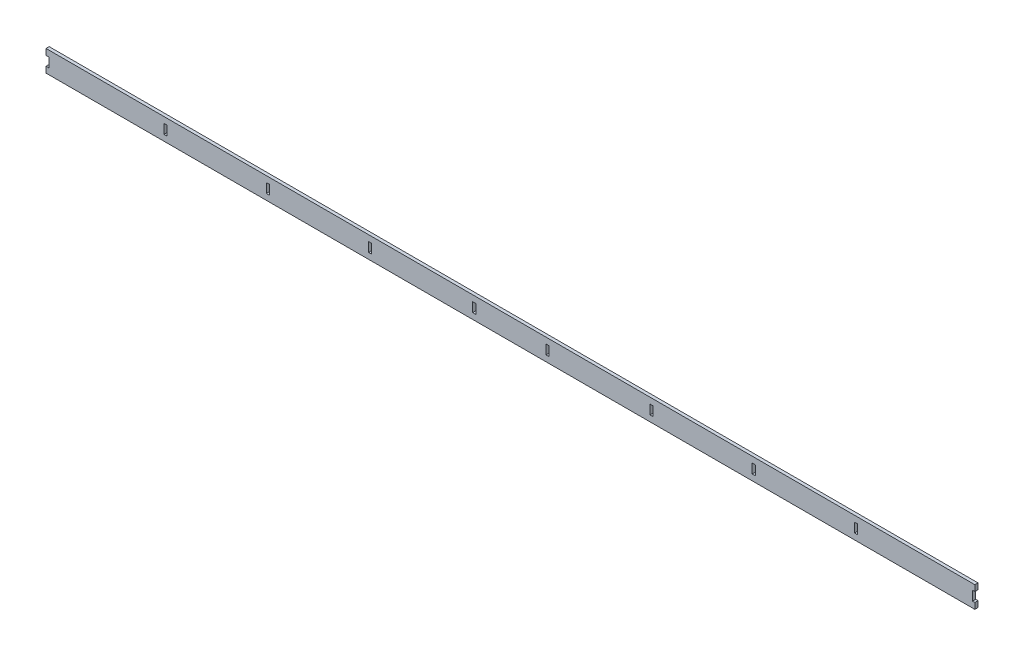
SolidWorks part; units mm, degrees
ref_plane "前视基准面" through (0, 0, 0) normal (0, 0, 1) x (1, 0, 0)
ref_plane "上视基准面" through (0, 0, 0) normal (0, 1, 0) x (1, 0, 0)
ref_plane "右视基准面" through (0, 0, 0) normal (1, 0, 0) x (0, 0, -1)
sketch "Model" plane through (0, 0, 0) normal (0, 0, 1) x (1, 0, 0)
  line L0 (587.3644, 20.9364) -> (-2.9318, 20.9364)
  line L1 (-2.9318, 20.9364) -> (-2.9318, 17.1364)
  line L2 (-2.9318, 11.1364) -> (-2.9318, 7.3364)
  line L3 (-2.9318, 7.3364) -> (587.3644, 7.3364)
  line L4 (587.3644, 20.9364) -> (587.3644, 17.1364)
  line L5 (587.3644, 11.1364) -> (587.3644, 7.3364)
  line L6 (587.3644, 17.1364) -> (585.8644, 17.1364)
  line L7 (585.8644, 17.1364) -> (585.8644, 11.1364)
  line L8 (585.8644, 11.1364) -> (587.3644, 11.1364)
  line L9 (-2.9318, 17.1364) -> (-0.9318, 17.1364)
  line L10 (-0.9318, 17.1364) -> (-0.9318, 11.1364)
  line L11 (-0.9318, 11.1364) -> (-2.9318, 11.1364)
  line L12 (72.0681, 14.1364) -> (72.0681, 17.1364)
  line L13 (72.0681, 11.1364) -> (72.0681, 14.1364)
  line L14 (137.0681, 14.1364) -> (137.0681, 17.1364)
  line L15 (137.0681, 11.1364) -> (137.0681, 14.1364)
  line L16 (202.0681, 14.1364) -> (202.0681, 17.1364)
  line L17 (202.0681, 11.1364) -> (202.0681, 14.1364)
  line L18 (268.2681, 14.1364) -> (268.2681, 17.1364)
  line L19 (268.2681, 11.1364) -> (268.2681, 14.1364)
  line L20 (314.7681, 14.1364) -> (314.7681, 17.1364)
  line L21 (314.7681, 11.1364) -> (314.7681, 14.1364)
  line L22 (380.8645, 14.1364) -> (380.8645, 17.1364)
  line L23 (380.8645, 11.1364) -> (380.8645, 14.1364)
  line L24 (445.8645, 14.1364) -> (445.8645, 17.1364)
  line L25 (445.8645, 11.1364) -> (445.8645, 14.1364)
  line L26 (510.8644, 14.1364) -> (510.8644, 17.1364)
  line L27 (510.8644, 11.1364) -> (510.8644, 14.1364)
  line L28 (72.0681, 17.1364) -> (74.0681, 17.1364)
  line L29 (74.0681, 17.1364) -> (74.0681, 11.1364)
  line L30 (74.0681, 11.1364) -> (72.0681, 11.1364)
  line L31 (137.0681, 17.1364) -> (139.0681, 17.1364)
  line L32 (139.0681, 17.1364) -> (139.0681, 11.1364)
  line L33 (139.0681, 11.1364) -> (137.0681, 11.1364)
  line L34 (202.0681, 17.1364) -> (204.0681, 17.1364)
  line L35 (204.0681, 17.1364) -> (204.0681, 11.1364)
  line L36 (204.0681, 11.1364) -> (202.0681, 11.1364)
  line L37 (268.2681, 17.1364) -> (270.2681, 17.1364)
  line L38 (270.2681, 17.1364) -> (270.2681, 11.1364)
  line L39 (270.2681, 11.1364) -> (268.2681, 11.1364)
  line L40 (314.7681, 17.1364) -> (316.7681, 17.1364)
  line L41 (316.7681, 17.1364) -> (316.7681, 11.1364)
  line L42 (316.7681, 11.1364) -> (314.7681, 11.1364)
  line L43 (380.8645, 17.1364) -> (382.8645, 17.1364)
  line L44 (382.8645, 17.1364) -> (382.8645, 11.1364)
  line L45 (382.8645, 11.1364) -> (380.8645, 11.1364)
  line L46 (445.8645, 17.1364) -> (447.8645, 17.1364)
  line L47 (447.8645, 17.1364) -> (447.8645, 11.1364)
  line L48 (447.8645, 11.1364) -> (445.8645, 11.1364)
  line L49 (510.8644, 17.1364) -> (512.8644, 17.1364)
  line L50 (512.8644, 17.1364) -> (512.8644, 11.1364)
  line L51 (512.8644, 11.1364) -> (510.8644, 11.1364)
extrude "凸台-拉伸1" add sketch "Model" along normal blind 2
